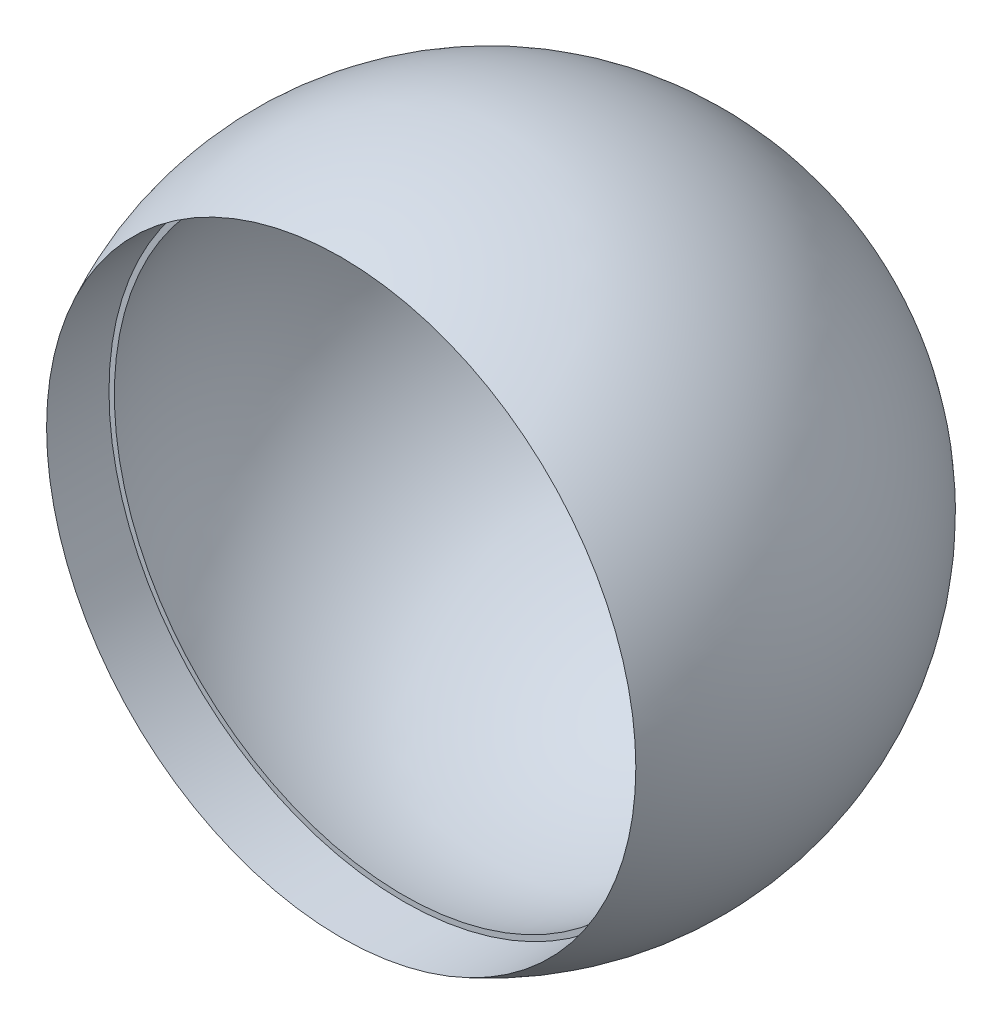
SolidWorks part; units mm, degrees
ref_plane "前视基准面" through (0, 0, 0) normal (0, 0, 1) x (1, 0, 0)
ref_plane "上视基准面" through (0, 0, 0) normal (0, 1, 0) x (1, 0, 0)
ref_plane "右视基准面" through (0, 0, 0) normal (1, 0, 0) x (0, 0, -1)
sketch "草图1" plane through (0, 0, 0) normal (0, 0, 1) x (1, 0, 0)
  line L0 (0, 235) -> (0, -235)
  arc A0 (0, -235) -> (0, 235) centre (0, 0) ccw
  arc A1 (0, -215) -> (0, 215) centre (0, 0) ccw
revolve "旋转1" add sketch "草图1" angle 360 about L0
sketch "草图2" plane through (0, 0, 0) normal (1, 0, 0) x (0, 0, -1)
  line L0 (87, 0) -> (-87, 0)
  point P4 (0, 0)
ref_plane "基准面1" through (0, 0, 235) normal (0, 0, 1) x (1, 0, 0)
sketch "草图3" plane through (0, 0, 235) normal (0, 0, 1) x (1, 0, 0)
  circle A0 centre (0, 0) radius 210
extrude "切除-拉伸1" cut sketch "草图3" against normal blind 174
